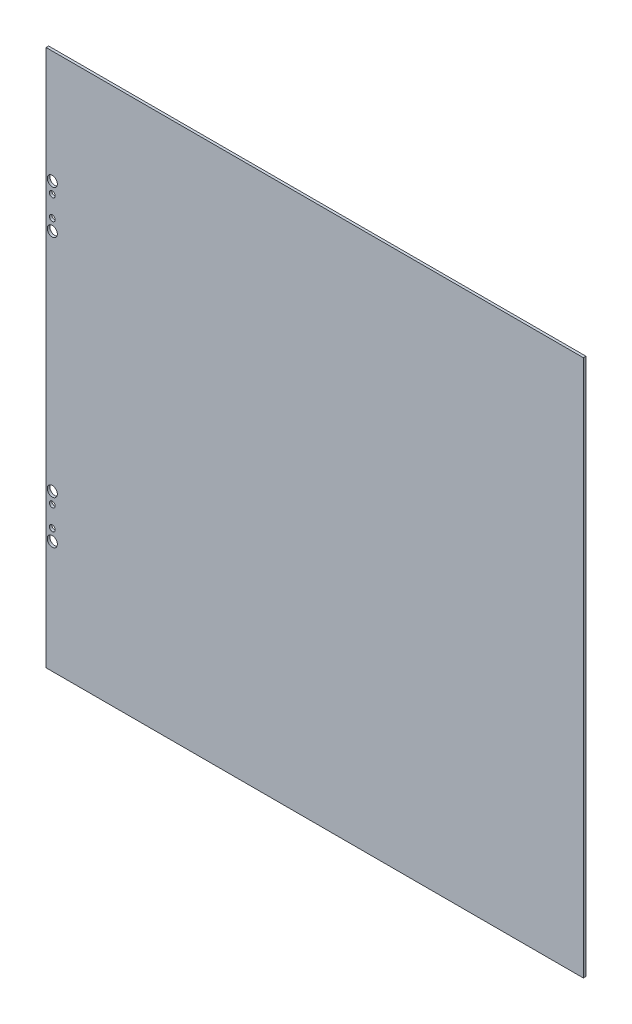
SolidWorks part; units mm, degrees
ref_plane "Front Plane" through (0, 0, 0) normal (0, 0, 1) x (1, 0, 0)
ref_plane "Top Plane" through (0, 0, 0) normal (0, 1, 0) x (1, 0, 0)
ref_plane "Right Plane" through (0, 0, 0) normal (1, 0, 0) x (0, 0, -1)
sketch "Sketch1" plane through (0, 0, 0) normal (0, 0, 1) x (1, 0, 0)
  line L0 (7.62, 508) -> (7.62, 482.6) construction
  line L1 (0, 0) -> (660.4, 0)
  line L2 (0, 0) -> (0, 660.4)
  line L3 (0, 660.4) -> (660.4, 660.4)
  line L4 (660.4, 0) -> (660.4, 660.4)
  line L5 (7.62, 177.8) -> (7.62, 152.4) construction
  line L6 (7.62, 495.3) -> (12.5606, 495.3) construction
  line L7 (7.62, 165.1) -> (16.0419, 165.1) construction
  circle A0 centre (7.62, 508) radius 3.556
  circle A1 centre (7.62, 482.6) radius 3.556
  circle A2 centre (7.62, 177.8) radius 3.556
  circle A3 centre (7.62, 152.4) radius 3.556
  circle A4 centre (7.62, 521.97) radius 6.1976
  circle A5 centre (7.62, 468.63) radius 6.1976
  circle A6 centre (7.62, 191.77) radius 6.1976
  circle A7 centre (7.62, 138.43) radius 6.1976
  dimension "D3" = 7.112
  dimension "D10" = 13.97
  dimension "D11" = 13.97
  dimension "D12" = 13.97
  dimension "D1" = 660.4
  dimension "D2" = 660.4
  dimension "D4" = 25.4
  dimension "D5" = 25.4
  dimension "D6" = 165.1
  dimension "D7" = 165.1
  dimension "D8" = 7.62
  dimension "D9" = 7.62
  dimension "D13" = 13.97
extrude "Boss-Extrude1" add sketch "Sketch1" along normal blind 3.175
